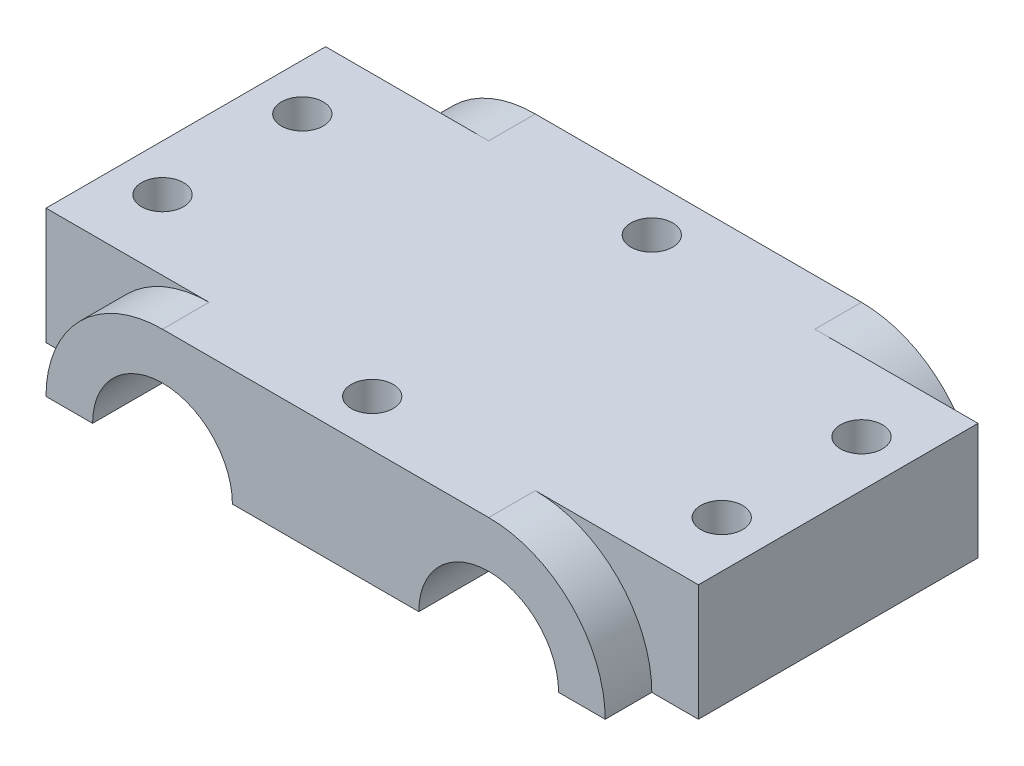
SolidWorks part; units mm, degrees
ref_plane "Front Plane" through (0, 0, 0) normal (0, 0, 1) x (1, 0, 0)
ref_plane "Top Plane" through (0, 0, 0) normal (0, 1, 0) x (1, 0, 0)
ref_plane "Right Plane" through (0, 0, 0) normal (1, 0, 0) x (0, 0, -1)
sketch "Sketch2" plane through (0, 0, 0) normal (0, 1, 0) x (1, 0, 0)
  line L1 (35, -15) -> (-35, -15)
  line L2 (35, -15) -> (35, 15)
  line L3 (35, 15) -> (-35, 15)
  line L4 (-35, -15) -> (-35, 15)
  line L5 (35, -15) -> (-35, 15) construction
  line L6 (35, 15) -> (-35, -15) construction
  point P0 (0, 0)
  dimension "D1" = 70
  dimension "D2" = 30
extrude "Boss-Extrude1" add sketch "Sketch2" along normal blind 12.5
sketch "Sketch3" plane through (0, 0, 15) normal (0, 0, 1) x (1, 0, 0)
  line L0 (0, 0) -> (0, 12.5) construction
  line L1 (-35, 12.5) -> (35, 12.5) construction
  line L2 (-35, 0) -> (35, 0) construction
  line L3 (17.5, 12.5) -> (-17.5, 12.5)
  line L4 (-30, 0) -> (-25, 0)
  line L5 (30, 0) -> (25, 0)
  line L6 (-10, 0) -> (10, 0)
  arc A0 (-17.5, 12.5) -> (-30, 0) centre (-17.5, 0) ccw
  arc A1 (-10, 0) -> (-25, 0) centre (-17.5, 0) ccw
  arc A2 (10, 0) -> (25, 0) centre (17.5, 0) cw
  arc A3 (17.5, 12.5) -> (30, 0) centre (17.5, 0) cw
  dimension "D1" = 7.5
  dimension "D3" = 12.5
  dimension "D2" = 17.5
extrude "Boss-Extrude2" add sketch "Sketch3" along normal blind 5 and the other way blind 35
sketch "Sketch4" plane through (0, 0, 15) normal (0, 0, 1) x (1, 0, 0)
  line L0 (-25, 0) -> (-10, 0) construction
  line L1 (10, 0) -> (25, 0) construction
  line L2 (-10, 0) -> (10, 0) construction
  line L3 (-25, 0) -> (-10, 0)
  line L4 (10, 0) -> (25, 0)
  arc A0 (-10, 0) -> (-25, 0) centre (-17.5, 0) ccw
  arc A1 (10, 0) -> (25, 0) centre (17.5, 0) cw
  arc A2 (25, 0) -> (10, 0) centre (17.5, 0) ccw construction
extrude "Cut-Extrude1" cut sketch "Sketch4" against normal through all
sketch "Sketch5" plane through (0, 12.5, 0) normal (0, 1, 0) x (1, 0, 0)
  line L0 (-35, 15) -> (-35, -15) construction
  line L1 (-35, -15) -> (-17.5, -15) construction
  line L2 (0, 0) -> (0, 20) construction
  line L3 (17.5, 20) -> (-17.5, 20) construction
  line L4 (0, 0) -> (34.1714, 0) construction
  circle A0 centre (0, -15) radius 2.25
  circle A1 centre (-30, -7.5) radius 2.25
  circle A2 centre (30, -7.5) radius 2.25
  circle A3 centre (30, 7.5) radius 2.25
  circle A4 centre (-30, 7.5) radius 2.25
  circle A5 centre (0, 15) radius 2.25
  dimension "D1" = 4.5
  dimension "D2" = 4.5
  dimension "D3" = 5
  dimension "D4" = 7.5
extrude "Cut-Extrude2" cut sketch "Sketch5" against normal through all
